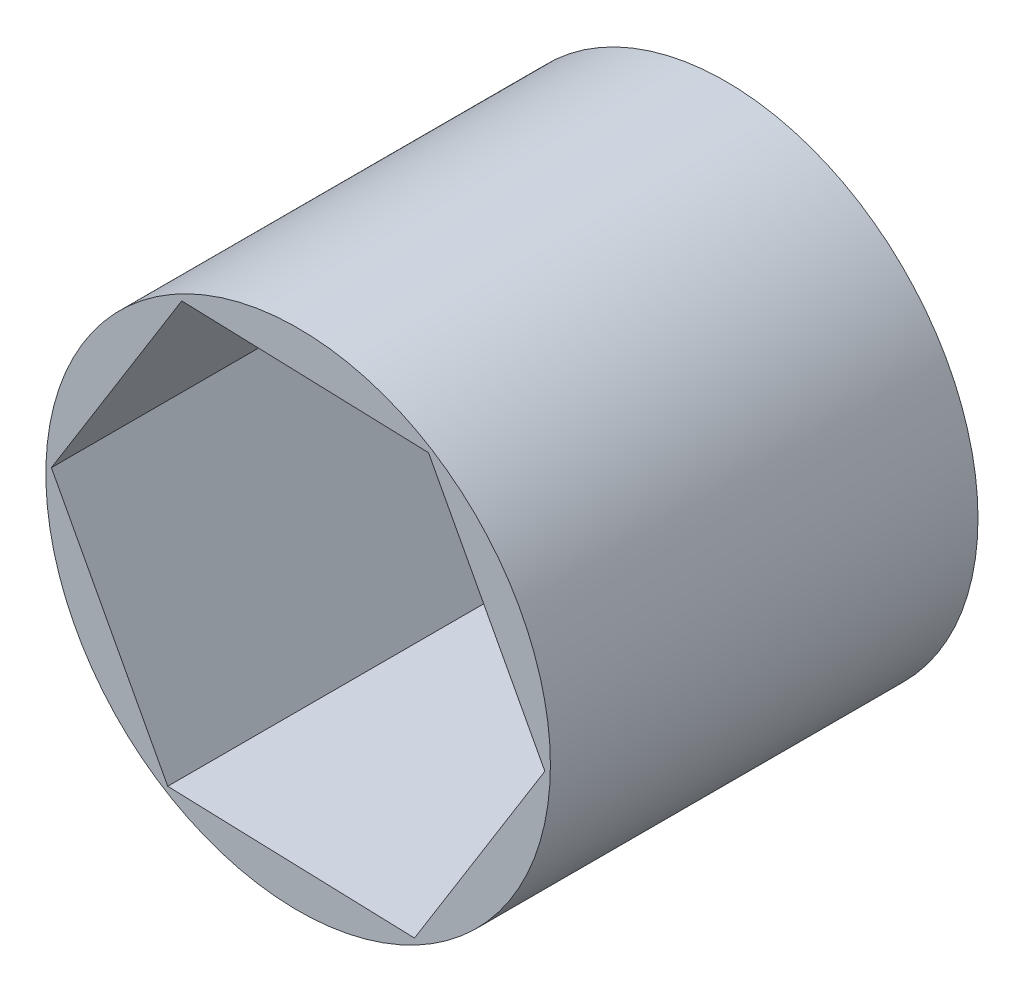
SolidWorks part; units mm, degrees
ref_plane "Front Plane" through (0, 0, 0) normal (0, 0, 1) x (1, 0, 0)
ref_plane "Top Plane" through (0, 0, 0) normal (0, 1, 0) x (1, 0, 0)
ref_plane "Right Plane" through (0, 0, 0) normal (1, 0, 0) x (0, 0, -1)
sketch "Sketch1" plane through (0, 0, 0) normal (0, 0, 1) x (1, 0, 0)
  line L1 (3.8725, 6.2263) -> (-3.4559, 6.4668)
  line L2 (-3.4559, 6.4668) -> (-7.3284, 0.2405)
  line L3 (-7.3284, 0.2405) -> (-3.8725, -6.2263)
  line L4 (-3.8725, -6.2263) -> (3.4559, -6.4668)
  line L5 (3.4559, -6.4668) -> (7.3284, -0.2405)
  line L6 (7.3284, -0.2405) -> (3.8725, 6.2263)
  circle A0 centre (0, 0) radius 7.493
  circle A1 centre (0, 0) radius 6.35 construction
  dimension "D1" = 14.986
  dimension "D2" = 12.7
extrude "Boss-Extrude1" add sketch "Sketch1" along normal blind 12.7
